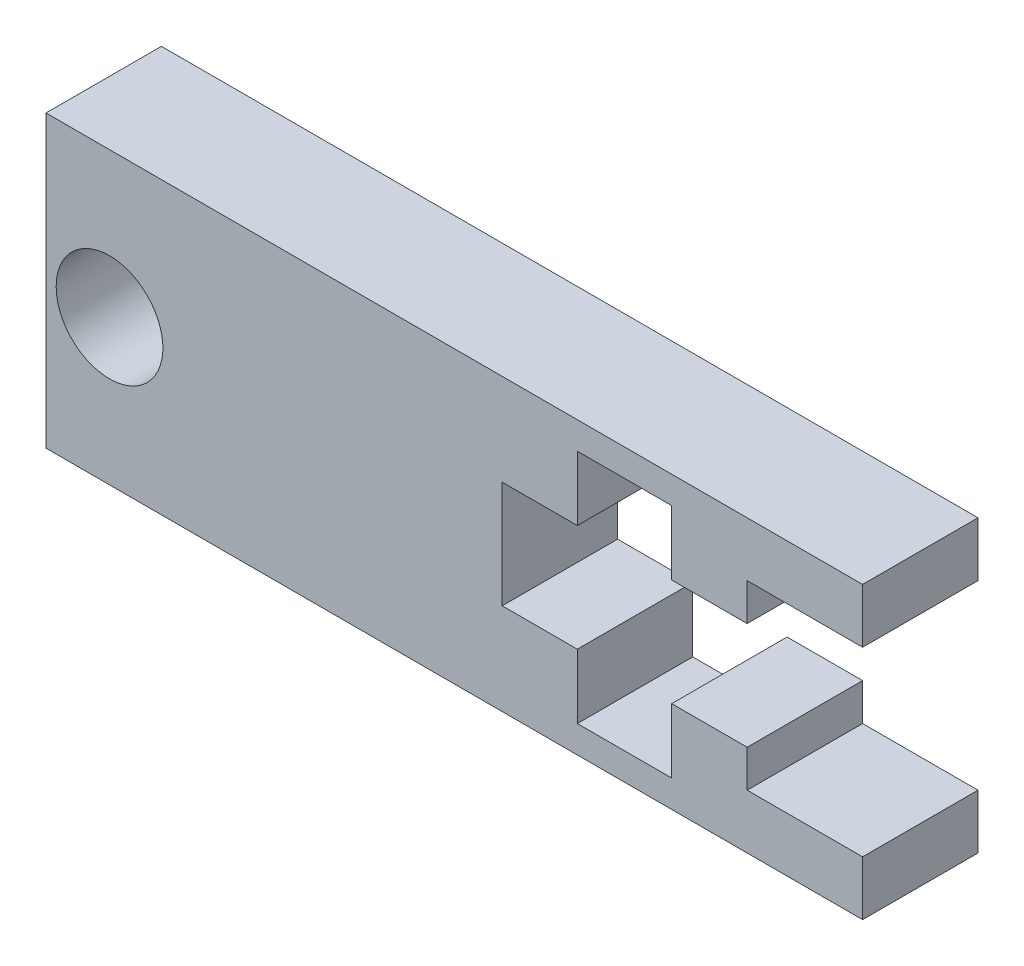
SolidWorks part; units mm, degrees
ref_plane "Front Plane" through (0, 0, 0) normal (0, 0, 1) x (1, 0, 0)
ref_plane "Top Plane" through (0, 0, 0) normal (0, 1, 0) x (1, 0, 0)
ref_plane "Right Plane" through (0, 0, 0) normal (1, 0, 0) x (0, 0, -1)
sketch "Sketch1" plane through (0, 0, 0) normal (0, 0, 1) x (1, 0, 0)
  line L0 (0, 0) -> (-11.25, 0) construction
  line L1 (-11.25, -4) -> (11.25, -4)
  line L2 (-11.25, -4) -> (-11.25, 4)
  line L3 (-11.25, 4) -> (11.25, 4)
  line L4 (11.25, -4) -> (11.25, 4)
  line L5 (-11.25, -4) -> (11.25, 4) construction
  line L6 (-11.25, 4) -> (11.25, -4) construction
  circle A0 centre (-9.5, 0) radius 1.47
  point P0 (0, 0)
  dimension "D3" = 2.94
  dimension "D1" = 8
  dimension "D2" = 1.75
  dimension "D4" = 22.5
extrude "Boss-Extrude1" add sketch "Sketch1" along normal mid plane 3.18
sketch "Sketch2" plane through (0, 0, -1.59) normal (0, 0, -1) x (-1, 0, 0)
  line L0 (-11.25, 0) -> (0, 0) construction
  line L1 (-11.25, -4) -> (-11.25, 4) construction
  line L2 (-3.39, -1.475) -> (-1.32, -1.475)
  line L3 (-11.25, -2.5) -> (-8.07, -2.5)
  line L4 (-11.25, -2.5) -> (-11.25, 2.5)
  line L5 (-11.25, 2.5) -> (-8.07, 2.5)
  line L6 (-8.07, -2.5) -> (-8.07, -1.475)
  line L7 (-8.07, 1.475) -> (-5.99, 1.475)
  line L9 (-8.07, -1.475) -> (-5.99, -1.475)
  line L10 (-1.32, 1.475) -> (-1.32, -1.475)
  line L15 (-3.39, -3.25) -> (-5.99, -3.25)
  line L16 (-3.39, -3.25) -> (-3.39, -1.475)
  line L17 (-3.39, 3.25) -> (-5.99, 3.25)
  line L18 (-5.99, -3.25) -> (-5.99, -1.475)
  line L19 (-3.39, 1.475) -> (-3.39, 3.25)
  line L20 (-3.39, 1.475) -> (-1.32, 1.475)
  line L21 (-5.99, 1.475) -> (-5.99, 3.25)
  line L22 (-8.07, 1.475) -> (-8.07, 2.5)
  dimension "D1" = 3.18
  dimension "D2" = 5
  dimension "D3" = 6.75
  dimension "D4" = 2.95
  dimension "D5" = 2.6
  dimension "D6" = 2.08
  dimension "D7" = 6.5
extrude "Cut-Extrude1" cut sketch "Sketch2" against normal through all
